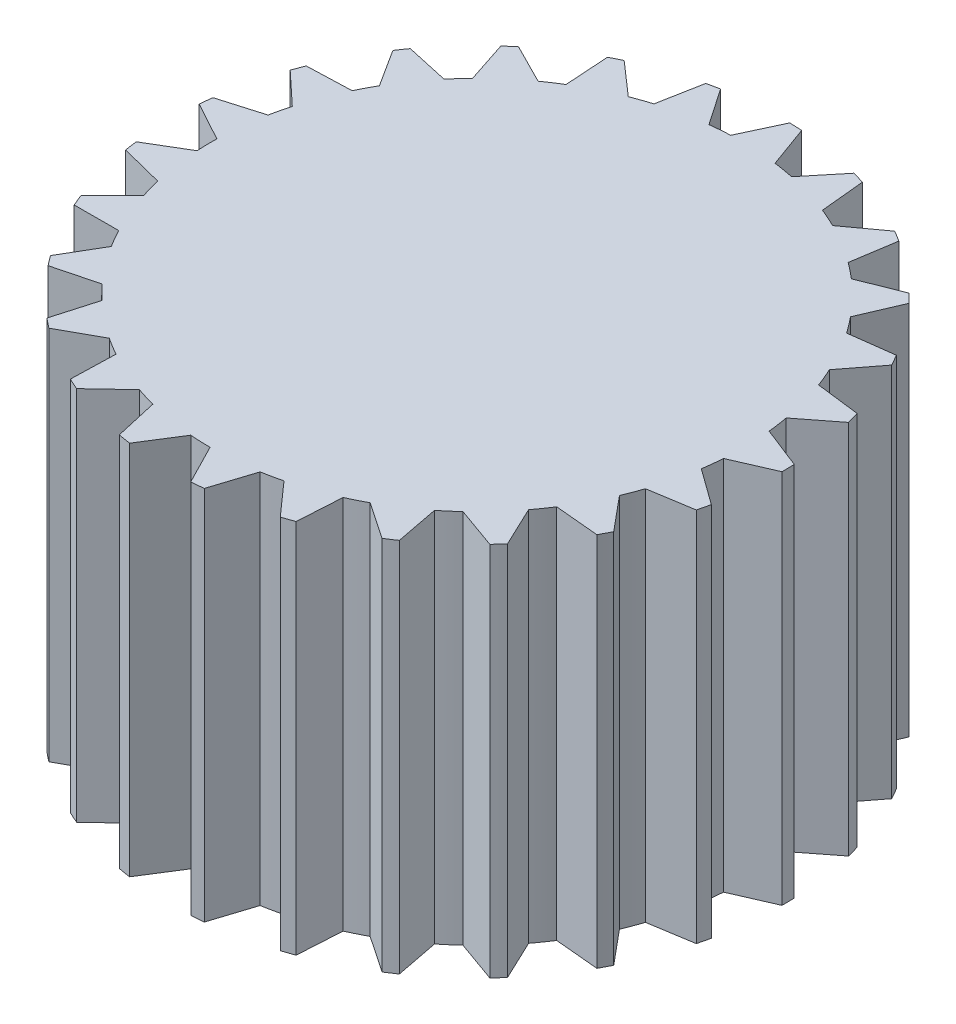
SolidWorks part; units mm, degrees
ref_plane "Front Plane" through (0, 0, 0) normal (0, 0, 1) x (1, 0, 0)
ref_plane "Top Plane" through (0, 0, 0) normal (0, 1, 0) x (1, 0, 0)
ref_plane "Right Plane" through (0, 0, 0) normal (1, 0, 0) x (0, 0, -1)
sketch "Sketch1" plane through (0, 0, 0) normal (0, 1, 0) x (1, 0, 0)
  circle A0 centre (0, 0) radius 2.65
  arc A3 (-1.8963, 1.8511) -> (-2.0313, 1.7018) centre (0, 0) ccw construction
extrude "Boss-Extrude1" add sketch "Sketch1" along normal blind 3.75
sketch "Sketch2" plane through (0, 0, 0) normal (0, -1, 0) x (-1, 0, 0)
  line L42 (-0.7494, 2.3063) -> (-0.3481, 2.1976)
  line L43 (-0.3481, 2.1976) -> (0, 2.425)
  line L44 (0, 2.425) -> (-0.3481, 2.1976) construction
  line L45 (0, 2.425) -> (0.3481, 2.1976)
  line L46 (0.3481, 2.1976) -> (0.7494, 2.3063)
  line L47 (0.7494, 2.3063) -> (1.0101, 1.9825)
  line L48 (1.0101, 1.9825) -> (1.4254, 1.9619)
  line L49 (1.4254, 1.9619) -> (1.5733, 1.5733)
  line L50 (1.5733, 1.5733) -> (1.9619, 1.4254)
  line L51 (1.9619, 1.4254) -> (1.9825, 1.0101)
  line L52 (1.9825, 1.0101) -> (2.3063, 0.7494)
  line L53 (2.3063, 0.7494) -> (2.1976, 0.3481)
  line L54 (2.1976, 0.3481) -> (2.425, 0)
  line L55 (2.425, 0) -> (2.1976, -0.3481)
  line L56 (2.1976, -0.3481) -> (2.3063, -0.7494)
  line L57 (2.3063, -0.7494) -> (1.9825, -1.0101)
  line L58 (1.9825, -1.0101) -> (1.9619, -1.4254)
  line L59 (1.9619, -1.4254) -> (1.5733, -1.5733)
  line L60 (1.5733, -1.5733) -> (1.4254, -1.9619)
  line L61 (1.4254, -1.9619) -> (1.0101, -1.9825)
  line L62 (1.0101, -1.9825) -> (0.7494, -2.3063)
  line L63 (0.7494, -2.3063) -> (0.3481, -2.1976)
  line L64 (0.3481, -2.1976) -> (0, -2.425)
  line L65 (0, -2.425) -> (-0.3481, -2.1976)
  line L66 (-0.3481, -2.1976) -> (-0.7494, -2.3063)
  line L67 (-0.7494, -2.3063) -> (-1.0101, -1.9825)
  line L68 (-1.0101, -1.9825) -> (-1.4254, -1.9619)
  line L69 (-1.4254, -1.9619) -> (-1.5733, -1.5733)
  line L70 (-1.5733, -1.5733) -> (-1.9619, -1.4254)
  line L71 (-1.9619, -1.4254) -> (-1.9825, -1.0101)
  line L72 (-1.9825, -1.0101) -> (-2.3063, -0.7494)
  line L73 (-2.3063, -0.7494) -> (-2.1976, -0.3481)
  line L74 (-2.1976, -0.3481) -> (-2.425, 0)
  line L75 (-2.425, 0) -> (-2.1976, 0.3481)
  line L76 (-2.1976, 0.3481) -> (-2.3063, 0.7494)
  line L77 (-2.3063, 0.7494) -> (-1.9825, 1.0101)
  line L78 (-1.9825, 1.0101) -> (-1.9619, 1.4254)
  line L79 (-1.9619, 1.4254) -> (-1.5733, 1.5733)
  line L80 (-1.5733, 1.5733) -> (-1.4254, 1.9619)
  line L81 (-1.4254, 1.9619) -> (-1.0101, 1.9825)
  line L82 (-1.0101, 1.9825) -> (-0.7494, 2.3063)
  circle A1 centre (0, 0) radius 2.425 construction
  point P69 (0, 0)
  dimension "D1" = 20
extrude "Cut-Extrude1" cut sketch "Sketch2" against normal blind 2.75
sketch "Sketch3" plane through (0, 3.75, 0) normal (0, 1, 0) x (1, 0, 0)
  line L0 (-2.6495, 0.0513) -> (-3.0386, 0.2638) construction
  line L1 (-2.6495, 0.0513) -> (-3.0386, 0.2638)
  line L2 (-2.5999, 0.5127) -> (-3.0252, 0.3878) construction
  line L3 (-2.5999, 0.5127) -> (-3.0252, 0.3878)
  line L4 (-2.3907, 1.1432) -> (-2.8337, 1.128)
  line L5 (-2.5535, 0.7086) -> (-2.8775, 1.0111)
  line L6 (-2.0313, 1.7018) -> (-2.4642, 1.7973)
  line L7 (-2.297, 1.3214) -> (-2.5357, 1.695)
  line L8 (-1.5443, 2.1535) -> (-1.9398, 2.3536)
  line L9 (-1.8963, 1.8511) -> (-2.0345, 2.2723)
  line L10 (-0.9602, 2.4699) -> (-1.2935, 2.7621)
  line L11 (-1.3763, 2.2646) -> (-1.4055, 2.7069)
  line L12 (-0.3158, 2.6311) -> (-0.566, 2.997)
  line L13 (-0.7699, 2.5357) -> (-0.6881, 2.9714)
  line L14 (0.3485, 2.627) -> (0.1971, 3.0436)
  line L15 (-0.1151, 2.6475) -> (0.0724, 3.0491)
  line L16 (0.9908, 2.4578) -> (0.9478, 2.899)
  line L17 (0.5469, 2.593) -> (0.8285, 2.9353)
  line L18 (1.5709, 2.1342) -> (1.639, 2.5722)
  line L19 (1.1746, 2.3755) -> (1.5324, 2.6371)
  line L20 (2.0523, 1.6764) -> (2.2272, 2.0838)
  line L21 (1.7284, 2.0088) -> (2.1401, 2.1731)
  line L22 (2.4048, 1.1134) -> (2.6754, 1.4644)
  line L23 (2.1737, 1.5158) -> (2.6133, 1.5726)
  line L24 (2.6061, 0.4804) -> (2.9556, 0.7531)
  line L25 (2.4823, 0.9276) -> (2.9223, 0.8733)
  line L26 (2.6437, -0.1828) -> (3.05, -0.0056)
  line L27 (2.635, 0.2811) -> (3.0477, 0.1192)
  line L28 (2.5152, -0.8346) -> (2.9528, -0.7639)
  line L29 (2.6222, -0.383) -> (2.9816, -0.6425)
  line L30 (2.2286, -1.4338) -> (2.67, -1.4743)
  line L31 (2.4445, -1.0231) -> (2.7281, -1.3638)
  line L32 (1.802, -1.943) -> (2.2195, -2.092)
  line L33 (2.1133, -1.5989) -> (2.3032, -1.9994)
  line L34 (1.2622, -2.3301) -> (1.6295, -2.5782)
  line L35 (1.6493, -2.0742) -> (1.7336, -2.5094)
  line L36 (0.643, -2.5708) -> (0.9372, -2.9025)
  line L37 (1.0817, -2.4192) -> (1.0551, -2.8617)
  line L38 (-0.0165, -2.6499) -> (0.1859, -3.0443)
  line L39 (0.446, -2.6122) -> (0.3103, -3.0342)
  line L40 (-0.675, -2.5626) -> (-0.577, -2.9949)
  line L41 (-0.2176, -2.6411) -> (-0.454, -3.016)
  line L42 (-1.2911, -2.3142) -> (-1.3037, -2.7573)
  line L43 (-0.8676, -2.504) -> (-1.1898, -2.8084)
  line L44 (-1.826, -1.9204) -> (-1.9485, -2.3465)
  line L45 (-1.463, -2.2095) -> (-1.8508, -2.4242)
  line L46 (-2.2463, -1.406) -> (-2.4708, -1.7882)
  line L47 (-1.9665, -1.7763) -> (-2.3956, -1.8878)
  line L48 (-2.5253, -0.8032) -> (-2.8379, -1.1176)
  line L49 (-2.3465, -1.2314) -> (-2.7898, -1.2327)
  line L50 (-2.6458, -0.1499) -> (-3.0266, -0.3767)
  line L51 (-2.579, -0.6092) -> (-3.0087, -0.5002)
  line L52 (0.7494, 2.3063) -> (0.3481, 2.1976) construction
  line L53 (0.3481, 2.1976) -> (0, 2.425) construction
  line L54 (0.7494, 2.3063) -> (0.3481, 2.1976)
  line L55 (0.3481, 2.1976) -> (0, 2.425)
  line L56 (1.4254, 1.9619) -> (1.0101, 1.9825)
  line L57 (1.0101, 1.9825) -> (0.7494, 2.3063)
  line L58 (1.9619, 1.4254) -> (1.5733, 1.5733)
  line L59 (1.5733, 1.5733) -> (1.4254, 1.9619)
  line L60 (2.3063, 0.7494) -> (1.9825, 1.0101)
  line L61 (1.9825, 1.0101) -> (1.9619, 1.4254)
  line L62 (2.425, 0) -> (2.1976, 0.3481)
  line L63 (2.1976, 0.3481) -> (2.3063, 0.7494)
  line L64 (2.3063, -0.7494) -> (2.1976, -0.3481)
  line L65 (2.1976, -0.3481) -> (2.425, 0)
  line L66 (1.9619, -1.4254) -> (1.9825, -1.0101)
  line L67 (1.9825, -1.0101) -> (2.3063, -0.7494)
  line L68 (1.4254, -1.9619) -> (1.5733, -1.5733)
  line L69 (1.5733, -1.5733) -> (1.9619, -1.4254)
  line L70 (0.7494, -2.3063) -> (1.0101, -1.9825)
  line L71 (1.0101, -1.9825) -> (1.4254, -1.9619)
  line L72 (0, -2.425) -> (0.3481, -2.1976)
  line L73 (0.3481, -2.1976) -> (0.7494, -2.3063)
  line L74 (-0.7494, -2.3063) -> (-0.3481, -2.1976)
  line L75 (-0.3481, -2.1976) -> (0, -2.425)
  line L76 (-1.4254, -1.9619) -> (-1.0101, -1.9825)
  line L77 (-1.0101, -1.9825) -> (-0.7494, -2.3063)
  line L78 (-1.9619, -1.4254) -> (-1.5733, -1.5733)
  line L79 (-1.5733, -1.5733) -> (-1.4254, -1.9619)
  line L80 (-2.3063, -0.7494) -> (-1.9825, -1.0101)
  line L81 (-1.9825, -1.0101) -> (-1.9619, -1.4254)
  line L82 (-2.425, 0) -> (-2.1976, -0.3481)
  line L83 (-2.1976, -0.3481) -> (-2.3063, -0.7494)
  line L84 (-2.3063, 0.7494) -> (-2.1976, 0.3481)
  line L85 (-2.1976, 0.3481) -> (-2.425, 0)
  line L86 (-1.9619, 1.4254) -> (-1.9825, 1.0101)
  line L87 (-1.9825, 1.0101) -> (-2.3063, 0.7494)
  line L88 (-1.4254, 1.9619) -> (-1.5733, 1.5733)
  line L89 (-1.5733, 1.5733) -> (-1.9619, 1.4254)
  line L90 (-0.7494, 2.3063) -> (-1.0101, 1.9825)
  line L91 (-1.0101, 1.9825) -> (-1.4254, 1.9619)
  line L92 (0, 2.425) -> (-0.3481, 2.1976)
  line L93 (-0.3481, 2.1976) -> (-0.7494, 2.3063)
  arc A0 (-2.6495, 0.0513) -> (-2.6458, -0.1499) centre (0, 0) ccw construction
  arc A1 (-3.0252, 0.3878) -> (-3.0386, 0.2638) centre (0, 0) ccw construction
  arc A2 (-2.6495, 0.0513) -> (-2.6458, -0.1499) centre (0, 0) ccw
  arc A3 (-3.0252, 0.3878) -> (-3.0386, 0.2638) centre (0, 0) ccw
  arc A4 (-2.8337, 1.128) -> (-2.8775, 1.0111) centre (0, 0) ccw
  arc A5 (-2.5535, 0.7086) -> (-2.5999, 0.5127) centre (0, 0) ccw
  arc A6 (-2.4642, 1.7973) -> (-2.5357, 1.695) centre (0, 0) ccw
  arc A7 (-2.297, 1.3214) -> (-2.3907, 1.1432) centre (0, 0) ccw
  arc A8 (-1.9398, 2.3536) -> (-2.0345, 2.2723) centre (0, 0) ccw
  arc A9 (-1.8963, 1.8511) -> (-2.0313, 1.7018) centre (0, 0) ccw
  arc A10 (-1.2935, 2.7621) -> (-1.4055, 2.7069) centre (0, 0) ccw
  arc A11 (-1.3763, 2.2646) -> (-1.5443, 2.1535) centre (0, 0) ccw
  arc A12 (-0.566, 2.997) -> (-0.6881, 2.9714) centre (0, 0) ccw
  arc A13 (-0.7699, 2.5357) -> (-0.9602, 2.4699) centre (0, 0) ccw
  arc A14 (0.1971, 3.0436) -> (0.0724, 3.0491) centre (0, 0) ccw
  arc A15 (-0.1151, 2.6475) -> (-0.3158, 2.6311) centre (0, 0) ccw
  arc A16 (0.9478, 2.899) -> (0.8285, 2.9353) centre (0, 0) ccw
  arc A17 (0.5469, 2.593) -> (0.3485, 2.627) centre (0, 0) ccw
  arc A18 (1.639, 2.5722) -> (1.5324, 2.6371) centre (0, 0) ccw
  arc A19 (1.1746, 2.3755) -> (0.9908, 2.4578) centre (0, 0) ccw
  arc A20 (2.2272, 2.0838) -> (2.1401, 2.1731) centre (0, 0) ccw
  arc A21 (1.7284, 2.0088) -> (1.5709, 2.1342) centre (0, 0) ccw
  arc A22 (2.6754, 1.4644) -> (2.6133, 1.5726) centre (0, 0) ccw
  arc A23 (2.1737, 1.5158) -> (2.0523, 1.6764) centre (0, 0) ccw
  arc A24 (2.9556, 0.7531) -> (2.9223, 0.8733) centre (0, 0) ccw
  arc A25 (2.4823, 0.9276) -> (2.4048, 1.1134) centre (0, 0) ccw
  arc A26 (3.05, -0.0056) -> (3.0477, 0.1192) centre (0, 0) ccw
  arc A27 (2.635, 0.2811) -> (2.6061, 0.4804) centre (0, 0) ccw
  arc A28 (2.9528, -0.7639) -> (2.9816, -0.6425) centre (0, 0) ccw
  arc A29 (2.6222, -0.383) -> (2.6437, -0.1828) centre (0, 0) ccw
  arc A30 (2.67, -1.4743) -> (2.7281, -1.3638) centre (0, 0) ccw
  arc A31 (2.4445, -1.0231) -> (2.5152, -0.8346) centre (0, 0) ccw
  arc A32 (2.2195, -2.092) -> (2.3032, -1.9994) centre (0, 0) ccw
  arc A33 (2.1133, -1.5989) -> (2.2286, -1.4338) centre (0, 0) ccw
  arc A34 (1.6295, -2.5782) -> (1.7336, -2.5094) centre (0, 0) ccw
  arc A35 (1.6493, -2.0742) -> (1.802, -1.943) centre (0, 0) ccw
  arc A36 (0.9372, -2.9025) -> (1.0551, -2.8617) centre (0, 0) ccw
  arc A37 (1.0817, -2.4192) -> (1.2622, -2.3301) centre (0, 0) ccw
  arc A38 (0.1859, -3.0443) -> (0.3103, -3.0342) centre (0, 0) ccw
  arc A39 (0.446, -2.6122) -> (0.643, -2.5708) centre (0, 0) ccw
  arc A40 (-0.577, -2.9949) -> (-0.454, -3.016) centre (0, 0) ccw
  arc A41 (-0.2176, -2.6411) -> (-0.0165, -2.6499) centre (0, 0) ccw
  arc A42 (-1.3037, -2.7573) -> (-1.1898, -2.8084) centre (0, 0) ccw
  arc A43 (-0.8676, -2.504) -> (-0.675, -2.5626) centre (0, 0) ccw
  arc A44 (-1.9485, -2.3465) -> (-1.8508, -2.4242) centre (0, 0) ccw
  arc A45 (-1.463, -2.2095) -> (-1.2911, -2.3142) centre (0, 0) ccw
  arc A46 (-2.4708, -1.7882) -> (-2.3956, -1.8878) centre (0, 0) ccw
  arc A47 (-1.9665, -1.7763) -> (-1.826, -1.9204) centre (0, 0) ccw
  arc A48 (-2.8379, -1.1176) -> (-2.7898, -1.2327) centre (0, 0) ccw
  arc A49 (-2.3465, -1.2314) -> (-2.2463, -1.406) centre (0, 0) ccw
  arc A50 (-3.0266, -0.3767) -> (-3.0087, -0.5002) centre (0, 0) ccw
  arc A51 (-2.579, -0.6092) -> (-2.5253, -0.8032) centre (0, 0) ccw
  point P130 (0, 0)
  point P166 (0, 0)
  dimension "D1" = 25
extrude "Boss-Extrude2" add sketch "Sketch3" against normal up to surface (3.75 mm away) up to face at (0, 0, 0)
